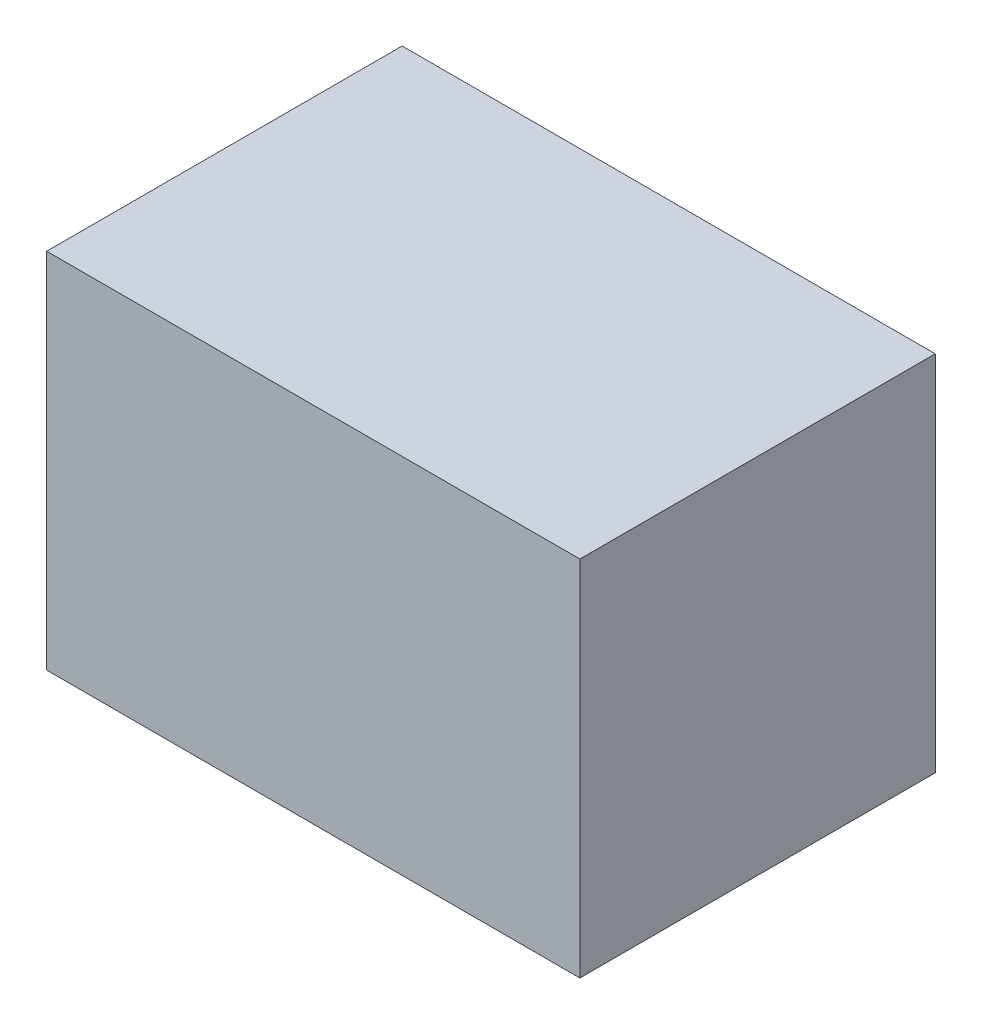
SolidWorks part; units mm, degrees
ref_plane "Front Plane" through (0, 0, 0) normal (0, 0, 1) x (1, 0, 0)
ref_plane "Top Plane" through (0, 0, 0) normal (0, 1, 0) x (1, 0, 0)
ref_plane "Right Plane" through (0, 0, 0) normal (1, 0, 0) x (0, 0, -1)
sketch "Sketch1" plane through (0, 0, 0) normal (0, 1, 0) x (1, 0, 0)
  line L1 (36, -24) -> (-36, -24)
  line L2 (36, -24) -> (36, 24)
  line L3 (36, 24) -> (-36, 24)
  line L4 (-36, -24) -> (-36, 24)
  line L5 (36, -24) -> (-36, 24) construction
  line L6 (36, 24) -> (-36, -24) construction
  point P0 (0, 0)
  dimension "D1" = 72
  dimension "D2" = 48
extrude "Boss-Extrude1" add sketch "Sketch1" along normal mid plane 49
